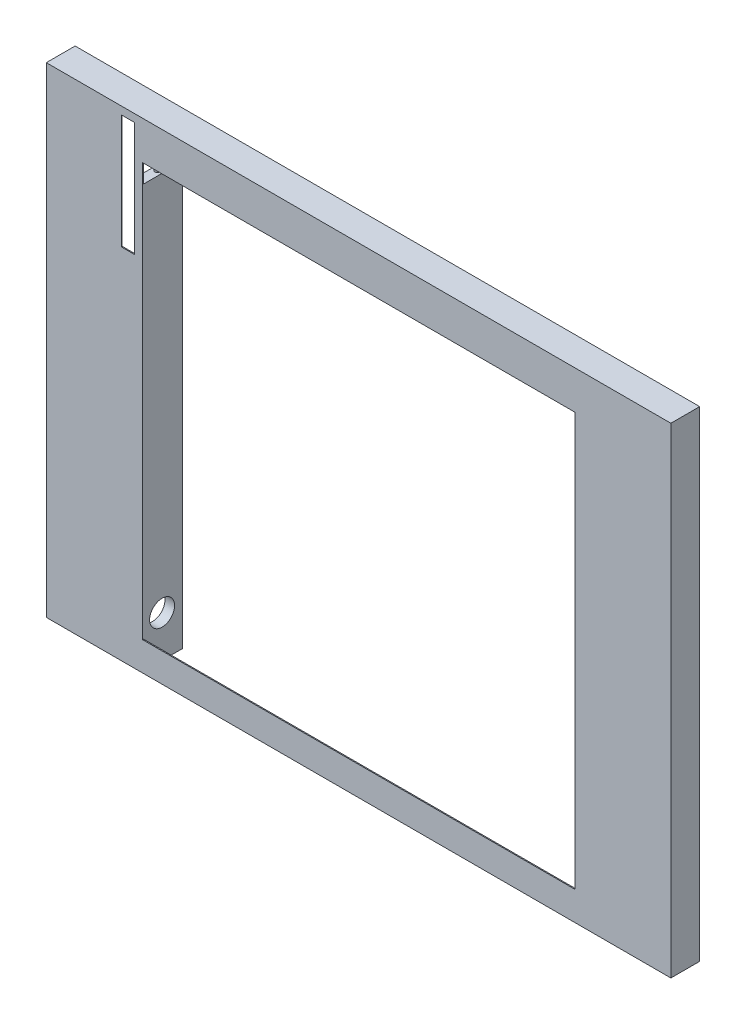
SolidWorks part; units mm, degrees
ref_plane "Front Plane" through (0, 0, 0) normal (0, 0, 1) x (1, 0, 0)
ref_plane "Top Plane" through (0, 0, 0) normal (0, 1, 0) x (1, 0, 0)
ref_plane "Right Plane" through (0, 0, 0) normal (1, 0, 0) x (0, 0, -1)
sketch "Sketch1" plane through (0, 0, 0) normal (0, 0, 1) x (1, 0, 0)
  line L1 (325, -250) -> (-325, -250)
  line L2 (325, -250) -> (325, 250)
  line L3 (325, 250) -> (-325, 250)
  line L4 (-325, -250) -> (-325, 250)
  line L5 (325, -250) -> (-325, 250) construction
  line L6 (325, 250) -> (-325, -250) construction
  line L7 (225, -210) -> (-225, -210)
  line L8 (225, -210) -> (225, 210)
  line L9 (225, 210) -> (-225, 210)
  line L10 (-225, -210) -> (-225, 210)
  line L11 (225, -210) -> (-225, 210) construction
  line L12 (225, 210) -> (-225, -210) construction
  point P0 (0, 0)
  point P6 (0, 0)
  dimension "D1" = 500
  dimension "D2" = 650
  dimension "D3" = 450
  dimension "D4" = 420
extrude "Boss-Extrude1" add sketch "Sketch1" along normal mid plane 30
shell "Shell1" thickness 1
sketch "Sketch3" plane through (0, 0, 0) normal (0, 0, 1) x (1, 0, 0)
  line L0 (-225, 210) -> (-225, -210) construction
  line L1 (225, -210) -> (-225, -210)
  line L2 (225, -210) -> (225, -220)
  line L3 (225, -220) -> (-225, -220)
  line L4 (-225, -210) -> (-225, -220)
  line L5 (-225, -210) -> (225, -210) construction
  line L6 (225, -210) -> (225, 210) construction
  dimension "D1" = 10
extrude "Cut-Extrude1" cut sketch "Sketch3" against normal mid plane 40
sketch "Sketch4" plane through (0, 0, 14) normal (0, 0, -1) x (-1, 0, 0)
  line L0 (225, 210) -> (225, -220) construction
  line L1 (225, 190) -> (225, -249)
  line L2 (324, -249) -> (-324, -249) construction
  line L3 (235, -249) -> (225, -249)
  line L4 (235, -249) -> (235, 190)
  line L7 (225, 190) -> (235, 190)
  line L8 (-225, 210) -> (225, 210) construction
  dimension "D1" = 10
  dimension "D2" = 20
extrude "Boss-Extrude2" add sketch "Sketch4" along normal blind 41
mirror "Mirror1" about plane through (0, 0, 0) normal (1, 0, 0) of "Boss-Extrude2"
sketch "Sketch5" plane through (-235, 0, 0) normal (-1, 0, 0) x (0, 0, 1)
  line L1 (15, 210) -> (15, -220) construction
  line L2 (15, -250) -> (-15, -250) construction
  circle A0 centre (-5.5, -206) radius 13
  dimension "D1" = 26
  dimension "D2" = 20.5
  dimension "D3" = 44
extrude "Cut-Extrude2" cut sketch "Sketch5" against normal blind 470
sketch "Sketch6" plane through (0, 190, 0) normal (0, 1, 0) x (1, 0, 0)
  line L0 (235, 27) -> (235, -14) construction
  line L1 (235, -14) -> (225, -14) construction
  circle A0 centre (230, 5.5) radius 2.5
  dimension "D1" = 5
  dimension "D2" = 5
  dimension "D3" = 19.5
extrude "Boss-Extrude3" add sketch "Sketch6" along normal blind 50
mirror "Mirror2" about plane through (0, 0, 0) normal (1, 0, 0) of "Boss-Extrude3"
sketch "Sketch7" plane through (0, 0, 15) normal (0, 0, 1) x (1, 0, 0)
  line L0 (-225, 210) -> (-225, -220) construction
  line L1 (-247, 242) -> (-233, 242)
  line L2 (-247, 242) -> (-247, 123)
  line L3 (-247, 123) -> (-233, 123)
  line L4 (-233, 242) -> (-233, 123)
  line L5 (325, 250) -> (-325, 250) construction
  dimension "D1" = 8
  dimension "D2" = 14
  dimension "D3" = 8
  dimension "D4" = 127
extrude "Cut-Extrude3" cut sketch "Sketch7" against normal blind 5
